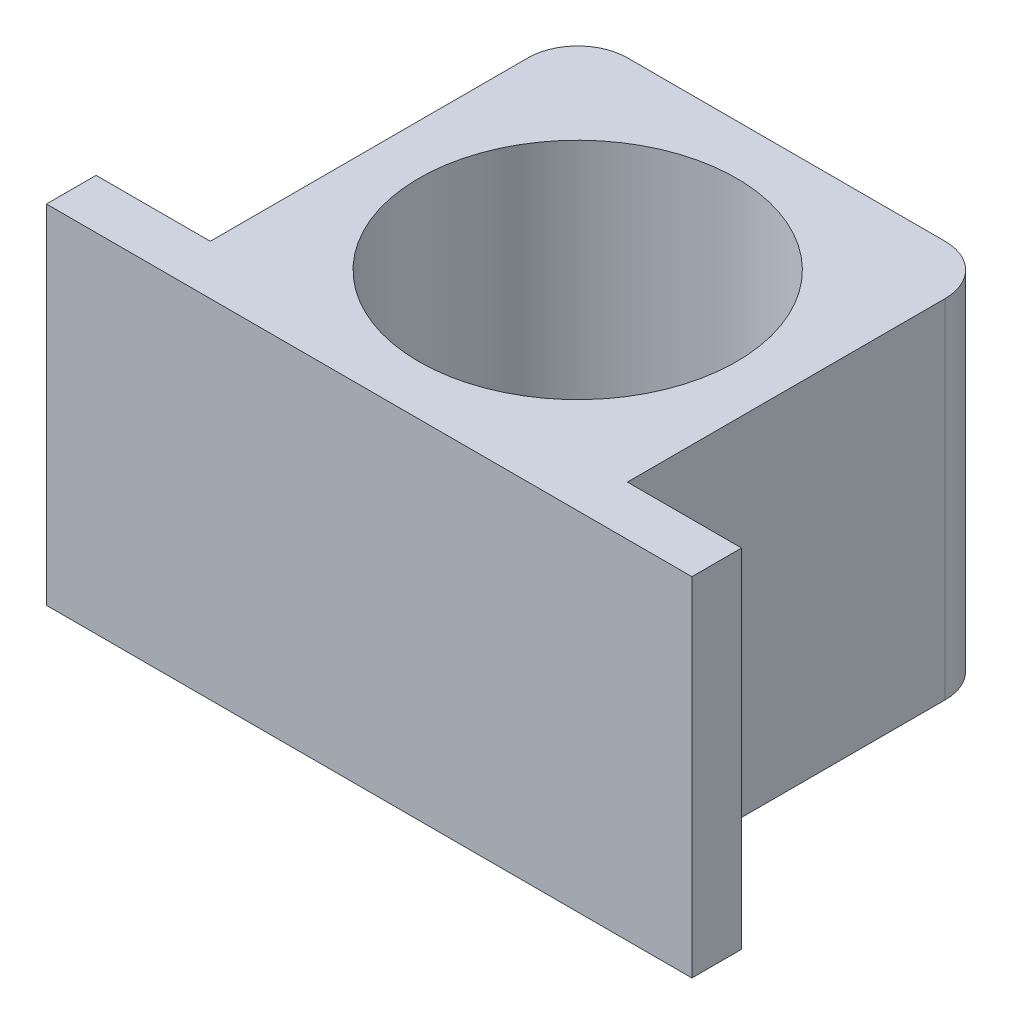
SolidWorks part; units mm, degrees
ref_plane "Front Plane" through (0, 0, 0) normal (0, 0, 1) x (1, 0, 0)
ref_plane "Top Plane" through (0, 0, 0) normal (0, 1, 0) x (1, 0, 0)
ref_plane "Right Plane" through (0, 0, 0) normal (1, 0, 0) x (0, 0, -1)
sketch "Sketch3" plane through (0, 0, 0) normal (0, 1, 0) x (1, 0, 0)
  line L1 (-27.5, 21) -> (27.5, 21)
  line L2 (-27.5, 21) -> (-27.5, -21)
  line L3 (-27.5, -21) -> (27.5, -21)
  line L4 (27.5, 21) -> (27.5, -21)
  line L5 (-27.5, 21) -> (27.5, -21) construction
  line L6 (-27.5, -21) -> (27.5, 21) construction
  point P0 (0, 0)
  dimension "D1" = 55
  dimension "D2" = 42
extrude "Boss-Extrude1" add sketch "Sketch3" along normal blind 35
sketch "Sketch4" plane through (0, 35, 0) normal (0, 1, 0) x (1, 0, 0)
  circle A0 centre (0, 0) radius 16
  dimension "D1" = 32
extrude "Cut-Extrude1" cut sketch "Sketch4" against normal blind 35
sketch "Sketch5" plane through (0, 35, 0) normal (0, 1, 0) x (1, 0, 0)
  line L0 (-27.5, -21) -> (27.5, -21) construction
  line L1 (-27.5, 21) -> (-21, 21)
  line L2 (-27.5, 21) -> (-27.5, -16)
  line L3 (-27.5, -16) -> (-21, -16)
  line L4 (-21, 21) -> (-21, -16)
  line L5 (0, 21) -> (0, -21) construction
  line L6 (27.5, 21) -> (-27.5, 21) construction
  line L7 (27.5, -16) -> (21, -16)
  line L8 (21, 21) -> (21, -16)
  line L9 (27.5, 21) -> (21, 21)
  line L10 (27.5, 21) -> (27.5, -16)
  circle A0 centre (0, 0) radius 16 construction
  dimension "D2" = 21
  dimension "D1" = 5
extrude "Cut-Extrude2" cut sketch "Sketch5" against normal blind 35
fillet "Fillet1" radius 5 2 edges at (-21, 17.5, -21) (21, 17.5, -21)
sketch "Sketch6" plane through (27.5, 0, 0) normal (1, 0, 0) x (0, 0, -1)
  line L1 (-21, 35) -> (-16, 35)
  line L2 (-21, 35) -> (-21, 0)
  line L3 (-21, 0) -> (-16, 0)
  line L4 (-16, 35) -> (-16, 0)
extrude "Boss-Extrude2" add sketch "Sketch6" along normal blind 5
sketch "Sketch7" plane through (-27.5, 0, 0) normal (-1, 0, 0) x (0, 0, 1)
  line L1 (16, 35) -> (21, 35)
  line L2 (16, 35) -> (16, 0)
  line L3 (16, 0) -> (21, 0)
  line L4 (21, 35) -> (21, 0)
extrude "Boss-Extrude3" add sketch "Sketch7" along normal blind 5
